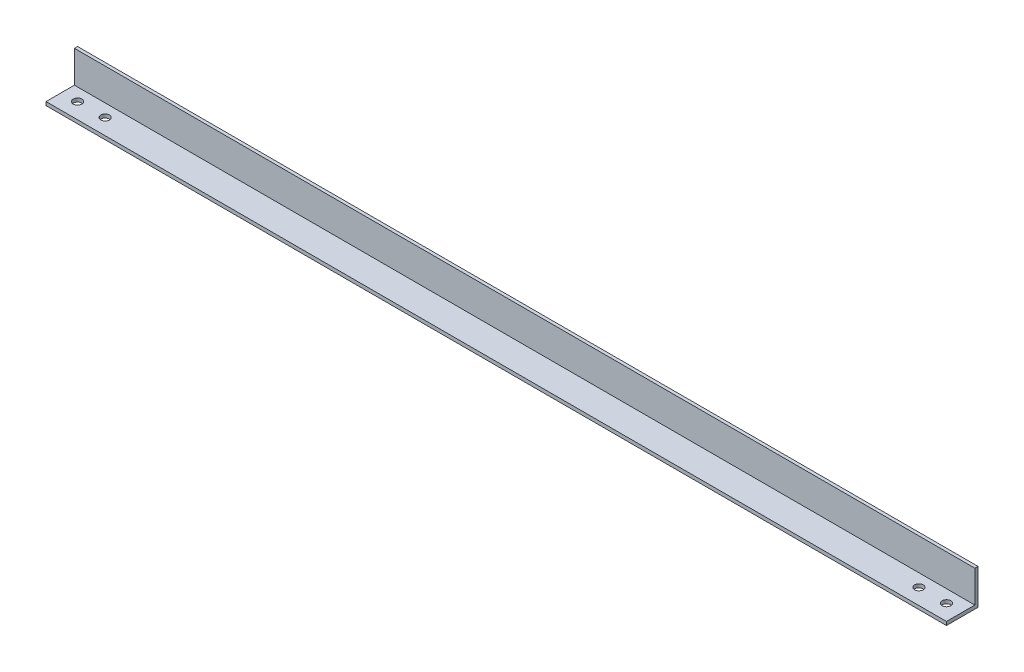
SolidWorks part; units mm, degrees
ref_plane "前视基准面" through (0, 0, 0) normal (0, 0, 1) x (1, 0, 0)
ref_plane "上视基准面" through (0, 0, 0) normal (0, 1, 0) x (1, 0, 0)
ref_plane "右视基准面" through (0, 0, 0) normal (1, 0, 0) x (0, 0, -1)
sketch "底面" plane through (0, 0, 0) normal (0, 0, 1) x (1, 0, 0)
  line L1 (0, 0) -> (2284, 0)
  line L2 (0, 0) -> (0, 90)
  line L3 (0, 90) -> (2284, 90)
  line L4 (2284, 0) -> (2284, 90)
  dimension "D1" = 2284
  dimension "D2" = 90
extrude "拉伸4" add sketch "底面" along normal blind 8
sketch "草图3" plane through (0, 0, 8) normal (0, 0, 1) x (1, 0, 0)
  line L1 (0, 0) -> (2284, 0)
  line L2 (0, 0) -> (0, 9)
  line L3 (0, 9) -> (2284, 9)
  line L4 (2284, 0) -> (2284, 9)
  dimension "D1" = 2284
  dimension "D2" = 9
extrude "拉伸5" add sketch "草图3" along normal blind 72
sketch "草图4" plane through (0, 9, 0) normal (0, 1, 0) x (1, 0, 0)
  line L3 (2284, -80) -> (0, -80) construction
  circle A0 centre (39.95, -40) radius 11
  circle A1 centre (109.95, -40) radius 11
  circle A2 centre (2174.05, -40) radius 11
  circle A3 centre (2244.05, -40) radius 11
  point P15 (1142, -80)
  dimension "D1" = 70
  dimension "D4" = 1032.05
  dimension "D2" = 70
  dimension "D3" = 2064.1
  dimension "D5" = 40
extrude "切除-拉伸2" cut sketch "草图4" against normal through all
